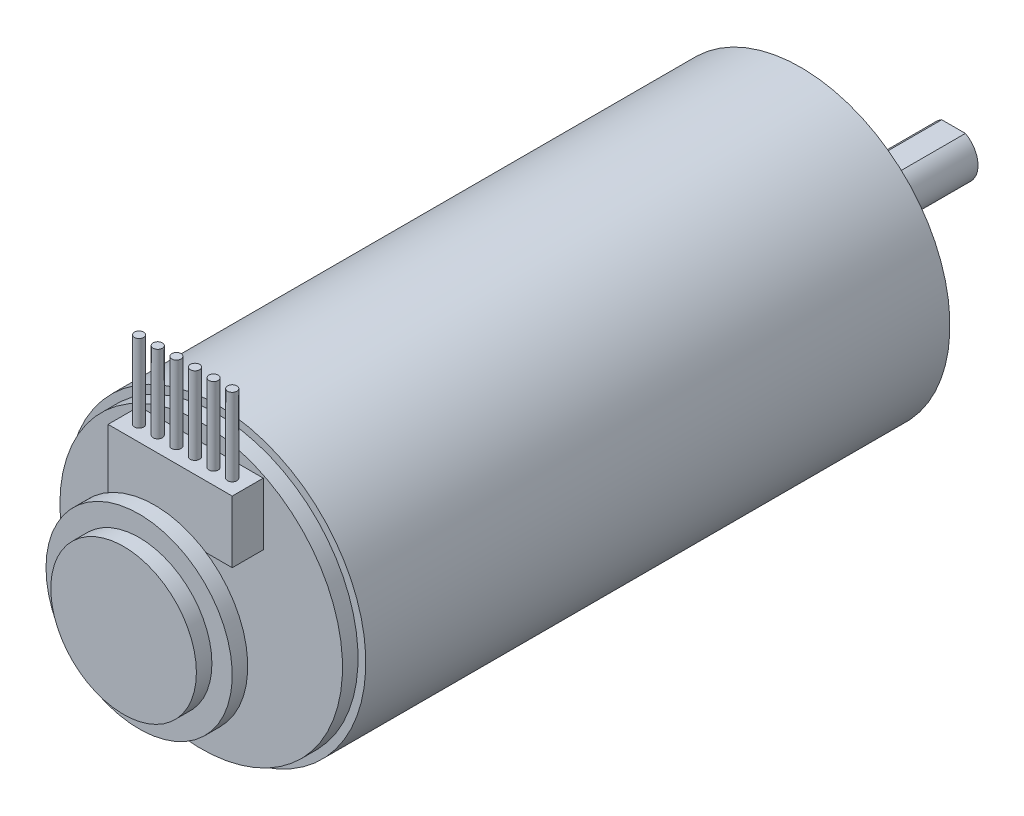
SolidWorks part; units mm, degrees
ref_plane "Front Plane" through (0, 0, 0) normal (0, 0, 1) x (1, 0, 0)
ref_plane "Top Plane" through (0, 0, 0) normal (0, 1, 0) x (1, 0, 0)
ref_plane "Right Plane" through (0, 0, 0) normal (1, 0, 0) x (0, 0, -1)
ref_plane "Plane1" through (0, 0, 0) normal (0, -1, 0) x (1, 0, 0)
sketch "Sketch1" plane through (0, 0, 0) normal (0, -1, 0) x (1, 0, 0)
  line L0 (7.62, 66.65) -> (0, 66.65)
  line L1 (0, 66.65) -> (0, 12.5)
  line L2 (0, 12.5) -> (12.2, 12.5)
  line L3 (12.2, 12.5) -> (12.2, 60.3)
  line L4 (12.2, 60.3) -> (11.565, 60.3)
  line L5 (11.565, 60.3) -> (11.565, 61.57)
  line L6 (11.565, 61.57) -> (1.27, 61.57)
  line L7 (1.27, 61.57) -> (1.27, 65.38)
  line L8 (1.27, 65.38) -> (7.62, 65.38)
  line L9 (7.62, 65.38) -> (7.62, 66.65)
  line L10 (0, 66.65) -> (0, 12.5) construction
revolve "Revolve1" add sketch "Sketch1" angle 360 about L10
sketch "Sketch2" plane through (0, 0, 12.5) normal (0, 0, -1) x (-1, 0, 0)
  circle A0 centre (0, 0) radius 3.5
extrude "Boss-Extrude1" add sketch "Sketch2" along normal blind 2.5
sketch "Sketch3" plane through (0, 0, 10) normal (0, 0, -1) x (-1, 0, 0)
  circle A0 centre (0, 0) radius 2
extrude "Boss-Extrude2" add sketch "Sketch3" along normal blind 10
sketch "Sketch4" plane through (0, 0, 0) normal (0, 0, -1) x (-1, 0, 0)
  line L0 (-0.9682, 1.75) -> (0.9682, 1.75)
  arc A0 (0.9682, 1.75) -> (-0.9682, 1.75) centre (0, 0) ccw
extrude "Cut-Extrude1" cut sketch "Sketch4" against normal blind 8
sketch "Sketch5" plane through (0, 0, 66.65) normal (0, 0, 1) x (1, 0, 0)
  circle A0 centre (0, 0) radius 5.9577
extrude "Boss-Extrude3" add sketch "Sketch5" along normal blind 1.27
sketch "Sketch6" plane through (0, 0, 61.57) normal (0, 0, 1) x (1, 0, 0)
  line L0 (5.08, 5.08) -> (-5.08, 5.08)
  line L1 (-5.08, 5.08) -> (-5.08, 10.16)
  line L2 (-5.08, 10.16) -> (5.08, 10.16)
  line L3 (5.08, 10.16) -> (5.08, 5.08)
extrude "Boss-Extrude4" add sketch "Sketch6" along normal blind 2.54
sketch "Sketch7" plane through (0, 10.16, 0) normal (0, 1, 0) x (-1, 0, 0)
  circle A0 centre (-2.286, 62.84) radius 0.381
extrude "Boss-Extrude5" add sketch "Sketch7" along normal blind 6.35
sketch "Sketch8" plane through (0, 10.16, 0) normal (0, 1, 0) x (-1, 0, 0)
  circle A0 centre (3.81, 62.84) radius 0.381
extrude "Boss-Extrude6" add sketch "Sketch8" along normal blind 6.35
sketch "Sketch9" plane through (0, 10.16, 0) normal (0, 1, 0) x (-1, 0, 0)
  circle A0 centre (0.762, 62.84) radius 0.381
extrude "Boss-Extrude7" add sketch "Sketch9" along normal blind 6.35
sketch "Sketch10" plane through (0, 10.16, 0) normal (0, 1, 0) x (-1, 0, 0)
  circle A0 centre (2.286, 62.84) radius 0.381
extrude "Boss-Extrude8" add sketch "Sketch10" along normal blind 6.35
sketch "Sketch11" plane through (0, 10.16, 0) normal (0, 1, 0) x (-1, 0, 0)
  circle A0 centre (-0.762, 62.84) radius 0.381
extrude "Boss-Extrude9" add sketch "Sketch11" along normal blind 6.35
sketch "Sketch12" plane through (0, 10.16, 0) normal (0, 1, 0) x (-1, 0, 0)
  circle A0 centre (-3.81, 62.84) radius 0.381
extrude "Boss-Extrude10" add sketch "Sketch12" along normal blind 6.35
